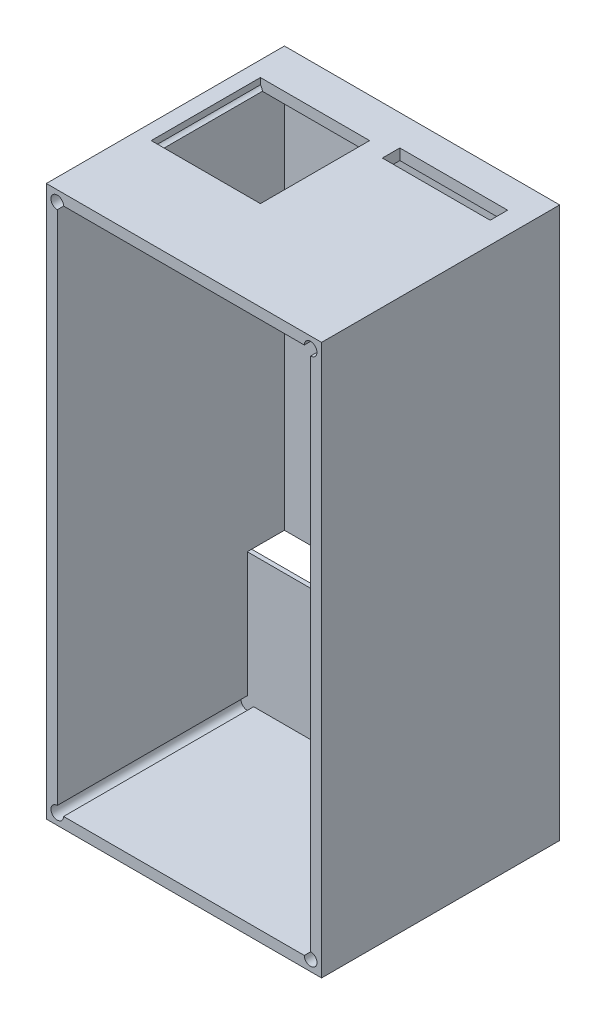
SolidWorks part; units mm, degrees
ref_plane "Front Plane" through (0, 0, 0) normal (0, 0, 1) x (1, 0, 0)
ref_plane "Top Plane" through (0, 0, 0) normal (0, 1, 0) x (1, 0, 0)
ref_plane "Right Plane" through (0, 0, 0) normal (1, 0, 0) x (0, 0, -1)
sketch "Sketch1" plane through (0, 0, 0) normal (0, 0, 1) x (1, 0, 0)
  line L0 (-31.5, 63) -> (-31.5, -63)
  line L1 (27.55, 60.5) -> (-27.55, 60.5)
  line L2 (29, 59.05) -> (29, -59.05)
  line L3 (27.55, -60.5) -> (-27.55, -60.5)
  line L4 (-29, 59.05) -> (-29, -59.05)
  line L5 (29, 60.5) -> (-29, -60.5) construction
  line L6 (29, -60.5) -> (-29, 60.5) construction
  line L7 (31.5, -63) -> (-31.5, -63)
  line L8 (31.5, 63) -> (31.5, -63)
  line L9 (31.5, 63) -> (-31.5, 63)
  line L11 (-29, 60.5) -> (-29, -60.5) construction
  line L12 (29, 60.5) -> (-29, 60.5) construction
  line L13 (29, 60.5) -> (29, -60.5) construction
  line L14 (29, -60.5) -> (-29, -60.5) construction
  circle A0 centre (-29, 60.5) radius 1.45
  circle A1 centre (29, 60.5) radius 1.45
  circle A2 centre (-29, -60.5) radius 1.45
  circle A3 centre (29, -60.5) radius 1.45
  point P0 (0, 0)
  dimension "D3" = 2.9
  dimension "D4" = 2.9
  dimension "D5" = 2.9
  dimension "D6" = 2.9
  dimension "D1" = 58
  dimension "D2" = 121
  dimension "D7" = 2.5
extrude "Boss-Extrude1" add sketch "Sketch1" along normal blind 52 contours L8 L9 L0 L7 A3 L3 A2 L4 A0 L1 A1 L2
sketch "Sketch2" plane through (0, 0, 0) normal (0, 0, -1) x (-1, 0, 0)
  line L1 (-31.5, 63) -> (31.5, 63)
  line L2 (-31.5, 63) -> (-31.5, -63)
  line L3 (-31.5, -63) -> (31.5, -63)
  line L4 (31.5, 63) -> (31.5, -63)
extrude "Boss-Extrude2" add sketch "Sketch2" along normal blind 2.5
sketch "Sketch4" plane through (0, 0, -2.5) normal (0, 0, -1) x (-1, 0, 0)
  line L1 (31.5, -63) -> (9, -63)
  line L2 (31.5, -63) -> (31.5, -30.5)
  line L3 (31.5, -30.5) -> (9, -30.5)
  line L4 (9, -63) -> (9, -30.5)
  dimension "D1" = 22.5
  dimension "D2" = 32.5
extrude "Cut-Extrude1" cut sketch "Sketch4" against normal blind 10
sketch "Sketch5" plane through (0, 0, 7.5) normal (0, 0, -1) x (-1, 0, 0)
  line L1 (31.5, -63) -> (9, -63)
  line L2 (31.5, -63) -> (31.5, -30.5)
  line L3 (31.5, -30.5) -> (9, -30.5)
  line L4 (9, -63) -> (9, -30.5)
extrude "Boss-Extrude3" add sketch "Sketch5" against normal blind 1
sketch "Sketch7" plane through (-9, 0, 0) normal (-1, 0, 0) x (0, 0, 1)
  line L1 (-2.5, -63) -> (7.5, -63)
  line L2 (-2.5, -63) -> (-2.5, -30.5)
  line L3 (-2.5, -30.5) -> (7.5, -30.5)
  line L4 (7.5, -63) -> (7.5, -30.5)
extrude "Boss-Extrude6" add sketch "Sketch7" along normal blind 1
sketch "Sketch8" plane through (0, 0, -2.5) normal (0, 0, -1) x (-1, 0, 0)
  line L0 (31.5, -30.5) -> (31.5, 63) construction
  line L1 (31.5, 63) -> (10.4, 63)
  line L2 (31.5, 63) -> (31.5, 39.2)
  line L3 (31.5, 39.2) -> (10.4, 39.2)
  line L4 (10.4, 63) -> (10.4, 39.2)
  line L5 (29, 39.2) -> (31.5, 39.2)
  line L6 (29, 39.2) -> (29, 20.8)
  line L7 (29, 20.8) -> (31.5, 20.8)
  line L8 (31.5, 39.2) -> (31.5, 20.8)
  line L10 (29, 39.2) -> (22, 39.2)
  line L11 (29, 39.2) -> (29, 20.8)
  line L12 (29, 20.8) -> (22, 20.8)
  line L13 (22, 39.2) -> (22, 20.8)
  line L14 (22, 39.2) -> (10.4, 39.2)
  line L15 (22, 39.2) -> (22, 20.8)
  line L16 (22, 20.8) -> (10.4, 20.8)
  line L17 (10.4, 39.2) -> (10.4, 20.8)
  dimension "D1" = 23.8
  dimension "D2" = 2.5
  dimension "D3" = 18.4
  dimension "D4" = 7
  dimension "D5" = 11.6
extrude "Cut-Extrude2" cut sketch "Sketch8" against normal through all contours L3 L17 L16 L13
sketch "Sketch9" plane through (0, 63, 0) normal (0, 1, 0) x (1, 0, 0)
  line L0 (31.5, -52) -> (31.5, 2.5) construction
  line L1 (-31.5, 2.5) -> (31.5, 2.5)
  line L2 (-31.5, 2.5) -> (-31.5, -6.5)
  line L3 (-31.5, -6.5) -> (31.5, -6.5)
  line L4 (31.5, 2.5) -> (31.5, -6.5)
  line L5 (-31.5, -52) -> (-31.5, 2.5) construction
  line L6 (-28, -6.5) -> (-3, -6.5)
  line L7 (-28, -6.5) -> (-28, -31.5)
  line L8 (-28, -31.5) -> (-3, -31.5)
  line L9 (-3, -6.5) -> (-3, -31.5)
  dimension "D1" = 9
  dimension "D2" = 25
  dimension "D3" = 25
  dimension "D4" = 0
  dimension "D5" = 3.5
extrude "Cut-Extrude3" cut sketch "Sketch9" against normal blind 11 contours L9 L3 L7 L8
sketch "Sketch10" plane through (0, 63, 0) normal (0, 1, 0) x (1, 0, 0)
  line L0 (-3, -6.5) -> (31.5, -6.5)
  line L1 (31.5, -52) -> (31.5, 2.5) construction
  line L3 (1.9142, -8.5) -> (26.5858, -8.5)
  line L4 (1.9142, -8.5) -> (1.9142, -4.5)
  line L5 (1.9142, -4.5) -> (26.5858, -4.5)
  line L6 (26.5858, -8.5) -> (26.5858, -4.5)
  line L7 (1.9142, -8.5) -> (26.5858, -4.5) construction
  line L8 (1.9142, -4.5) -> (26.5858, -8.5) construction
  point P5 (14.25, -6.5)
  dimension "D1" = 4
extrude "Cut-Extrude4" cut sketch "Sketch10" against normal blind 11 contours L3 L6 L0 L4 | L0 L6 L5 L4
